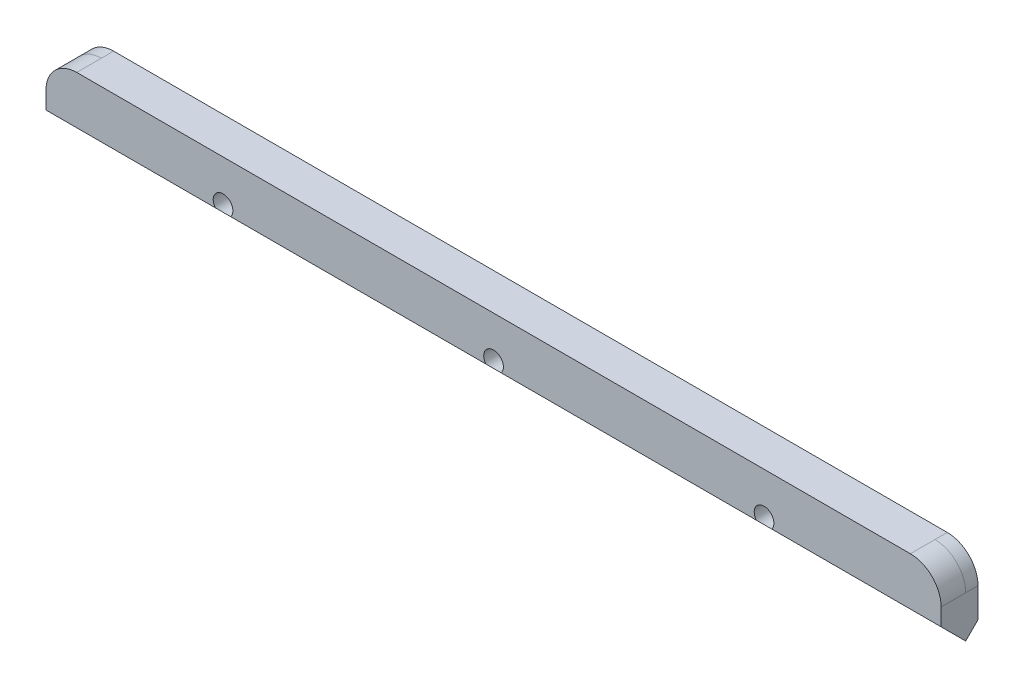
SolidWorks part; units mm, degrees
material "6061-T6 (SS)"
ref_plane "Front Plane" through (0, 0, 0) normal (0, 0, 1) x (1, 0, 0)
ref_plane "Top Plane" through (0, 0, 0) normal (0, 1, 0) x (1, 0, 0)
ref_plane "Right Plane" through (0, 0, 0) normal (1, 0, 0) x (0, 0, -1)
sketch "Sketch1" plane through (0, 0, 0) normal (1, 0, 0) x (0, 0, -1)
  line L0 (-3.0983, 0) -> (1.226, 0) construction
  line L1 (0, -3.2) -> (-2, -1.2)
  line L2 (0, -3.2) -> (0, 3.2)
  line L4 (-2, -1.2) -> (-2, 3.2)
  line L5 (-2, 3.2) -> (0, 3.2)
  dimension "D1" = 2
  dimension "D2" = 45
  dimension "D3" = 6.4
extrude "Boss-Extrude1" add sketch "Sketch1" along normal mid plane 72.8
fillet "Fillet3" radius 2.5 2 edges at (-36.4, 3.2, 1) (36.4, 3.2, 1)
sketch "Sketch5" plane through (-36.4, 0, 0) normal (-1, 0, 0) x (0, 0, 1)
  line L0 (0, -2.7) -> (2, -0.7)
  line L1 (0, -3.2) -> (0, 0.7) construction
  line L2 (2, 0.7) -> (2, -1.2) construction
  line L3 (2, -1.2) -> (0, -3.2) construction
  line L4 (2, -1.2) -> (2, -0.7)
  line L5 (2, -1.2) -> (0, -3.2)
  line L6 (0, -3.2) -> (0, -2.7)
  dimension "D1" = 0.5
extrude "Cut-Extrude5" cut sketch "Sketch5" against normal up to surface (72.8 mm away) up to face at (36.4, -0.75, 1)
sketch "Sketch7" plane through (-36.4, 0, 0) normal (-1, 0, 0) x (0, 0, 1)
  line L0 (0, -2.7) -> (-1, -1.7)
  line L1 (-1, -1.7) -> (-1, 3.2)
  line L2 (-1, 3.2) -> (0, 3.2)
  line L3 (0, 3.2) -> (0, -2.7)
  line L4 (0, 3.2) -> (2, 3.2) construction
  dimension "D1" = 45
  dimension "D2" = 3
extrude "Boss-Extrude2" add sketch "Sketch7" against normal up to surface (72.8 mm away) up to face at (36.4, -0.5, 1)
hole_wizard "M2x0.4 Tapped Hole1" positions "Sketch2" profile "Sketch3" tap size "M2x0.4" standard "ANSI Metric"
sketch "Sketch2" plane through (0, 0, 2) normal (0, 0, 1) x (1, 0, 0)
  circle A4 centre (-22, -0.2) radius 1.2 construction
  circle A5 centre (-22, -0.2) radius 1.2
  circle A8 centre (22, -0.2) radius 1.2 construction
  circle A9 centre (22, -0.2) radius 1.2
  circle A10 centre (0, -0.2) radius 1.2
  point P22 (-22, -0.2)
  point P28 (22, -0.2)
  point P31 (0, -0.2)
cosmetic thread "Hole Thread4" parameters "D1"=3, "D2"=2
cosmetic thread "Hole Thread6" parameters "D1"=3, "D2"=2
sketch "Sketch3" plane through (-22, -0.2, 2) normal (1, 0, 0) x (0, -1, 0)
  line L0 (0, 0) -> (0, 4.0807)
  line L1 (0, 4.0807) -> (0.8, 3.6)
  line L2 (0.8, 3.6) -> (0.8, 0)
  line L5 (0.8, 0) -> (0, 0)
  line L10 (0, 4.0807) -> (-0.8, 3.6) construction
  line L11 (0, -6.35) -> (0, 107.95) construction
  dimension "Tap Drill Dia." = 1.6
  dimension "Tap Drill Depth" = 3.6
  dimension "Drill Angle" = 118
cosmetic thread "Hole Thread7" parameters "D1"=3, "D2"=2
fillet "Fillet4" radius 2.5 2 edges at (-36.4, 3.2, -0.5) (36.4, 3.2, -0.5)
sketch "Sketch4" [suppressed] plane through (0, 0, 0) normal (0, 0, 1) x (1, 0, 0)
  line L1 (7.5, 1.5) -> (-7.5, 1.5)
  line L2 (7.5, 1.5) -> (7.5, -3.2)
  line L3 (7.5, -3.2) -> (-7.5, -3.2)
  line L4 (-7.5, 1.5) -> (-7.5, -3.2)
  line L5 (0, 7.7759) -> (0, -8.8374) construction
  line L8 (-7.5, -1.7) -> (-7.5, -0.7) construction
  dimension "D1" = 4.7
extrude "Cut-Extrude4" [suppressed] cut sketch "Sketch4" along normal mid plane 10
sketch "Sketch8" [suppressed] plane through (36.4, 0, 0) normal (1, 0, 0) x (0, 0, -1)
  line L1 (-1, -3.2) -> (-2, -2.2)
  line L2 (-2, -2.2) -> (-2, -1.2)
  line L3 (-2, -1.2) -> (0, -3.2)
  line L4 (0, -3.2) -> (-1, -3.2)
  dimension "D1" = 1
extrude "Boss-Extrude3" [suppressed] add sketch "Sketch8" against normal blind 3
sketch "Sketch10" [suppressed] plane through (7.5, 0, 0) normal (-1, 0, 0) x (0, 0, 1)
  line L1 (1, -3.2) -> (2, -2.2)
  line L2 (2, -2.2) -> (2, -1.2)
  line L3 (2, -1.2) -> (0, -3.2)
  line L4 (2, -2.2) -> (1, -3.2) construction
  line L5 (0, -3.2) -> (1, -3.2)
extrude "Boss-Extrude5" [suppressed] add sketch "Sketch10" against normal blind 3
mirror "Mirror1" [suppressed] about plane through (0, 0, 0) normal (1, 0, 0)
sketch "Sketch11" [suppressed] plane through (36.4, 0, 0) normal (1, 0, 0) x (0, 0, -1)
  line L0 (0, -2.7) -> (-1, -2.7)
  line L1 (-1, -2.7) -> (-2, -1.7)
  line L2 (-2, -1.7) -> (-2, -0.7)
  line L3 (0, -2.7) -> (-2, -0.7)
  dimension "D1" = 1
extrude "Boss-Extrude6" [suppressed] add sketch "Sketch11" against normal blind 3
sketch "Sketch12" [suppressed] plane through (7.5, 0, 0) normal (-1, 0, 0) x (0, 0, 1)
  line L0 (0, -2.7) -> (1, -2.7)
  line L1 (1, -2.7) -> (2, -1.7)
  line L2 (2, -1.7) -> (2, -0.7)
  line L3 (0, -2.7) -> (2, -0.7)
  line L4 (1, -2.7) -> (0, -2.7) construction
  line L5 (2, -1.7) -> (1, -2.7) construction
extrude "Boss-Extrude7" [suppressed] add sketch "Sketch12" against normal blind 3
mirror "Mirror7" [suppressed] about plane through (0, 0, 0) normal (1, 0, 0)
sketch "Sketch13" plane through (0, 0, 2) normal (0, 0, 1) x (1, 0, 0)
  line L0 (24.4, 3.2) -> (24.4, -2.7)
  line L1 (33.9, 3.2) -> (-33.9, 3.2) construction
  line L2 (36.4, -2.7) -> (-36.4, -2.7) construction
  line L4 (24.4, -2.7) -> (36.4, -2.7)
  line L5 (36.4, -2.7) -> (36.4, 3.2)
  line L6 (36.4, 3.2) -> (24.4, 3.2)
  dimension "D1" = 12
extrude "Cut-Extrude6" [suppressed] cut sketch "Sketch13" against normal up to surface (3 mm away)
